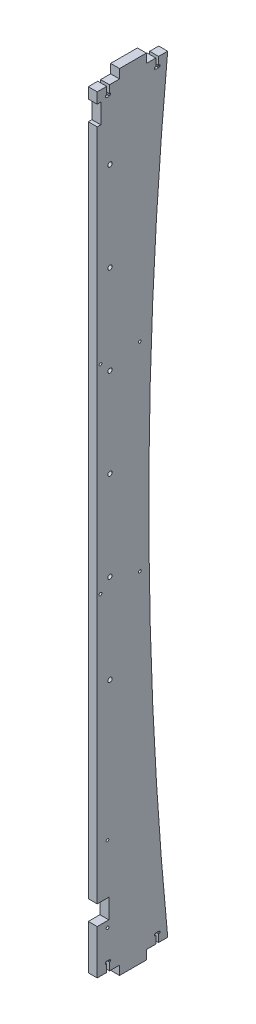
SolidWorks part; units mm, degrees
ref_plane "Płaszczyzna przednia" through (0, 0, 0) normal (0, 0, 1) x (1, 0, 0)
ref_plane "Płaszczyzna górna" through (0, 0, 0) normal (0, 1, 0) x (1, 0, 0)
ref_plane "Płaszczyzna prawa" through (0, 0, 0) normal (1, 0, 0) x (0, 0, -1)
ref_plane "Płaszczyzna2" through (248.5228, 0, 0) normal (-1, 0, 0) x (0, 0, 1)
sketch "Szkic11" plane through (248.5228, 0, 0) normal (-1, 0, 0) x (0, 0, 1)
  line L0 (-79.0014, 0) -> (0, 0)
  line L1 (0, 880) -> (-78.9552, 880)
  line L2 (-78.9552, 870) -> (-78.9552, 880)
  line L4 (-79.0014, 10) -> (-79.0014, 0)
  line L13 (0, 0) -> (0, 880)
  arc A2 (-79.0014, 10) -> (-78.9552, 870) centre (-4437.8003, 440.2341) ccw
extrude "Dodanie-wyciągnięcie1" add sketch "Szkic11" along normal blind 10
sketch "Szkic1" plane through (248.5228, 0, 0) normal (1, 0, 0) x (0, 0, -1)
  line L0 (85, 880) -> (85, 869.9)
  line L1 (85, 880) -> (55, 880)
  line L2 (85, 869.9) -> (55, 869.9)
  line L3 (55, 880) -> (55, 869.9)
  line L5 (25, 880) -> (25, 869.9)
  line L6 (25, 880) -> (0, 880)
  line L7 (25, 869.9) -> (0, 869.9)
  line L8 (0, 880) -> (0, 869.9)
  line L9 (0, 880) -> (78.9552, 880) construction
  dimension "D1" = 25
  dimension "D2" = 30
  dimension "D3" = 30
  dimension "D4" = 10.1
  dimension "D5" = 10.1
  dimension "D6" = 0
extrude "Wytnij-wyciągnięcie1" cut sketch "Szkic1" against normal blind 10
sketch "Szkic2" plane through (248.5228, 0, 0) normal (1, 0, 0) x (0, 0, -1)
  line L0 (10.6609, 869.9) -> (13.7609, 869.9)
  line L1 (10.6609, 869.9) -> (10.6609, 861.4)
  line L2 (13.7609, 869.9) -> (13.7609, 861.4)
  line L3 (10.6609, 858.9) -> (13.7609, 858.9)
  line L5 (9.2859, 859.4) -> (10.6609, 859.4)
  line L6 (9.2859, 859.4) -> (9.2859, 861.4)
  line L7 (15.1359, 859.4) -> (15.1359, 861.4)
  line L8 (9.2859, 861.4) -> (10.6609, 861.4)
  line L9 (13.7609, 859.4) -> (15.1359, 859.4)
  line L10 (10.6609, 859.4) -> (10.6609, 858.9)
  line L11 (13.7609, 859.4) -> (13.7609, 858.9)
  line L12 (13.7609, 861.4) -> (15.1359, 861.4)
  line L13 (0, 869.9) -> (25, 869.9) construction
  dimension "D1" = 11
  dimension "D2" = 5.85
  dimension "D3" = 3.1
  dimension "D4" = 1.375
  dimension "D5" = 2
  dimension "D6" = 0.5
  dimension "D7" = 0
extrude "Wytnij-wyciągnięcie2" cut sketch "Szkic2" against normal blind 10
pattern_linear "Szyk liniowy1" count 2 spacing 55 along (0, 0, -1) of "Wytnij-wyciągnięcie2"
ref_plane "Płaszczyzna1" through (0, 440, 0) normal (0, 1, 0) x (1, 0, 0)
sketch "Szkic4" plane through (248.5228, 0, 0) normal (-1, 0, 0) x (0, 0, 1)
  line L0 (-40, 133) -> (-25, 133) construction
  line L1 (-25, 133) -> (-25, 123) construction
  line L2 (-40, 123) -> (-25, 123) construction
  line L3 (-40, 133) -> (-40, 123) construction
  line L4 (-40, 48) -> (-25, 48) construction
  line L5 (-25, 58) -> (-25, 48) construction
  line L6 (-40, 58) -> (-25, 58) construction
  line L7 (-40, 58) -> (-40, 48) construction
  line L8 (-40, 133) -> (-25, 133)
  line L9 (-25, 133) -> (-25, 123)
  line L10 (-40, 123) -> (-25, 123)
  line L11 (-40, 133) -> (-40, 123)
  line L12 (-40, 48) -> (-25, 48)
  line L13 (-25, 58) -> (-25, 48)
  line L14 (-40, 58) -> (-25, 58)
  line L15 (-40, 58) -> (-40, 48)
  line L16 (-40.2, 122.8) -> (-24.8, 122.8)
  line L17 (-24.8, 133.2) -> (-24.8, 122.8)
  line L18 (-40.2, 133.2) -> (-24.8, 133.2)
  line L19 (-40.2, 133.2) -> (-40.2, 122.8)
  line L20 (-40.2, 47.8) -> (-24.8, 47.8)
  line L21 (-24.8, 58.2) -> (-24.8, 47.8)
  line L22 (-40.2, 58.2) -> (-24.8, 58.2)
  line L23 (-40.2, 58.2) -> (-40.2, 47.8)
  line L24 (-10, 58) -> (-10, 48) construction
  line L25 (-13.1, 58) -> (-13.1, 48) construction
  line L26 (-10, 133) -> (-10, 123) construction
  line L27 (-13.1, 133) -> (-13.1, 123) construction
  line L28 (-10, 58) -> (-10, 48)
  line L29 (-13.1, 58) -> (-13.1, 48)
  line L30 (-10, 133) -> (-10, 123)
  line L31 (-13.1, 133) -> (-13.1, 123)
  line L32 (-10, 128) -> (-13.1, 128)
  line L33 (-10, 53) -> (-13.1, 53)
  circle A0 centre (-11.55, 53) radius 1.55
  circle A1 centre (-11.55, 128) radius 1.55
  dimension "D2" = 3.1
  dimension "D3" = 3.1
  dimension "D1" = 0.2
sketch "Szkic5" plane through (248.5228, 0, 0) normal (-1, 0, 0) x (0, 0, 1)
  circle A0 centre (-11.55, 53) radius 1.55 construction
  circle A2 centre (-11.55, 53) radius 1.55
  circle A3 centre (-11.55, 138) radius 1.55 construction
  circle A4 centre (-11.55, 138) radius 1.55
extrude "Wytnij-wyciągnięcie3" cut sketch "Szkic5" along normal blind 10
sketch "Szkic7" plane through (248.5228, 0, 0) normal (1, 0, 0) x (0, 0, -1)
  circle A1 centre (14.3107, 792.237) radius 2.45 construction
  circle A2 centre (14.3107, 792.237) radius 2.45
extrude "Wytnij-wyciągnięcie5" cut sketch "Szkic7" against normal blind 10
pattern_linear "Szyk liniowy3" count 6 spacing 100 along (0, -1, 0) of "Wytnij-wyciągnięcie5"
sketch "Szkic8" plane through (248.5228, 0, 0) normal (1, 0, 0) x (0, 0, -1)
  line L3 (13, 60) -> (13, 82)
  line L4 (0, 60) -> (13, 60)
  line L5 (13, 82) -> (0, 82)
  line L6 (0, 60) -> (0, 82)
  line L7 (13, 60) -> (13, 82) construction
  line L8 (0, 0) -> (0, 869.9) construction
  line L9 (13, 82) -> (0, 82) construction
  line L10 (0, 60) -> (13, 60) construction
  dimension "D1" = 0
  dimension "D2" = 0
  dimension "D3" = 0
  dimension "D4" = 0
extrude "Wytnij-wyciągnięcie6" cut sketch "Szkic8" against normal blind 10
sketch "Szkic9" plane through (248.5228, 0, 0) normal (1, 0, 0) x (0, 0, -1)
  line L0 (0, 869.9) -> (10.6609, 869.9) construction
  line L1 (0, 835.9) -> (0, 857.9)
  line L2 (0, 835.9) -> (4, 835.9)
  line L3 (0, 857.9) -> (4, 857.9)
  line L4 (4, 835.9) -> (4, 857.9)
  dimension "D1" = 22
  dimension "D2" = 4
  dimension "D3" = 12
extrude "Wytnij-wyciągnięcie7" cut sketch "Szkic9" against normal blind 10
mirror "Lustro1" about plane through (0, 440, 0) normal (0, 1, 0) of "Szyk liniowy1", "Wytnij-wyciągnięcie2", "Wytnij-wyciągnięcie1"
sketch "Szkic12" plane through (238.5228, 0, 0) normal (-1, 0, 0) x (0, 0, 1)
  circle A0 centre (-47.7, 603.737) radius 1.55 construction
  circle A3 centre (-47.7, 603.737) radius 1.55
  circle A4 centre (-3.7, 603.737) radius 1.55 construction
  circle A5 centre (-3.7, 603.737) radius 1.55
extrude "Wytnij-wyciągnięcie8" cut sketch "Szkic12" against normal blind 10
pattern_linear "Szyk liniowy4" count 2 spacing 223 along (0, -1, 0) of "Wytnij-wyciągnięcie8"
equation "\"tolerancja_wpusy\"=0.2"
equation "\"dlugosc_wpustu_duzy\"=20"
equation "\"srednica_otworu_M3\"=3.1"
equation "\"szerokosc_nogi_T\"=3.1"
equation "\"dlugosc_T_30\"=11"
equation "\"grubosc_na_nakretke_kwadrat\"=2"
equation "\"szerokosc_na_nakretke_kwadrat\"=5.85"
equation "\"wyokosc_nadstawki_T\"=0.5"
equation "\"D1@Szkic2\"=\"dlugosc_T_30\""
equation "\"D2@Szkic2\"=\"szerokosc_na_nakretke_kwadrat\""
equation "\"D3@Szkic2\"=\"szerokosc_nogi_T\""
equation "\"D4@Szkic2\"=(\"szerokosc_na_nakretke_kwadrat\"-\"szerokosc_nogi_T\")/2"
equation "\"D5@Szkic2\"=\"grubosc_na_nakretke_kwadrat\""
equation "\"D6@Szkic2\"=\"wyokosc_nadstawki_T\""
equation "\"D2@Szkic4\"=\"srednica_otworu_M3\""
equation "\"D3@Szkic4\"=\"srednica_otworu_M3\""
